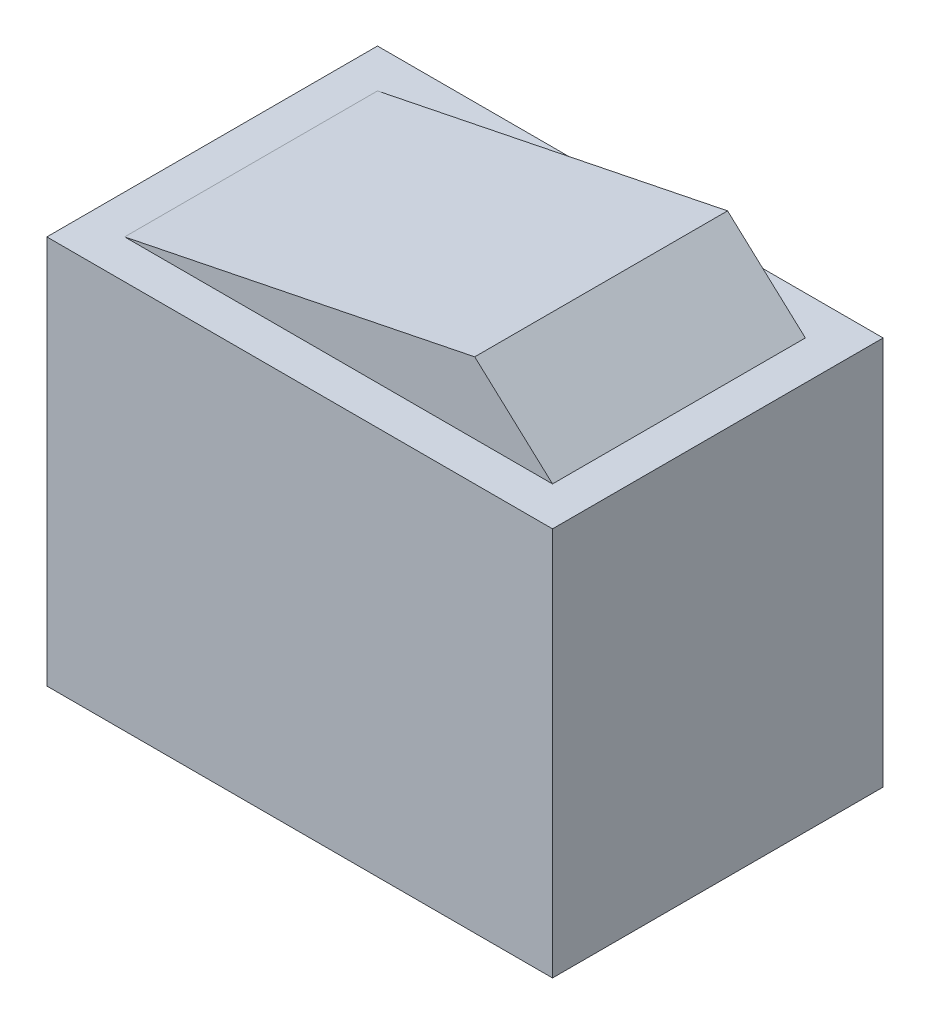
SolidWorks part; units mm, degrees
ref_plane "Front Plane" through (0, 0, 0) normal (0, 0, 1) x (1, 0, 0)
ref_plane "Top Plane" through (0, 0, 0) normal (0, 1, 0) x (1, 0, 0)
ref_plane "Right Plane" through (0, 0, 0) normal (1, 0, 0) x (0, 0, -1)
sketch "Sketch1" plane through (0, 0, 0) normal (0, 1, 0) x (1, 0, 0)
  line L1 (-6.5, 4.25) -> (6.5, 4.25)
  line L2 (-6.5, 4.25) -> (-6.5, -4.25)
  line L3 (-6.5, -4.25) -> (6.5, -4.25)
  line L4 (6.5, 4.25) -> (6.5, -4.25)
  line L5 (-6.5, 4.25) -> (6.5, -4.25) construction
  line L6 (-6.5, -4.25) -> (6.5, 4.25) construction
  point P0 (0, 0)
  dimension "D1" = 13
  dimension "D2" = 8.5
extrude "Boss-Extrude1" add sketch "Sketch1" along normal blind 10
ref_plane "Plane1" through (0, 0, 3.25) normal (0, 0, 1) x (1, 0, 0)
sketch "Sketch2" plane through (0, 0, 3.25) normal (0, 0, 1) x (1, 0, 0)
  line L0 (-5.5, 10) -> (5.5, 10)
  line L1 (-6.5, 10) -> (6.5, 10) construction
  line L2 (5.5, 10) -> (3.5, 11.8297)
  line L3 (3.5, 11.8297) -> (-5.5, 10)
  dimension "D1" = 1
  dimension "D2" = 1
  dimension "D3" = 9
  dimension "D4" = 9.1841
extrude "Boss-Extrude2" add sketch "Sketch2" against normal blind 6.5
